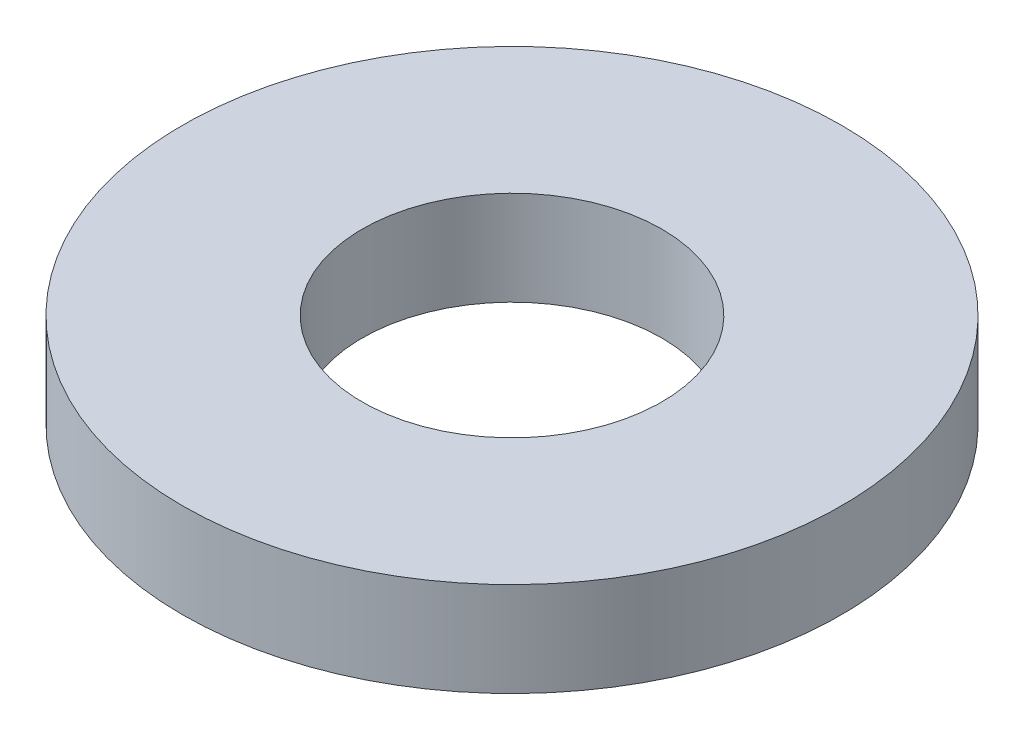
SolidWorks part; units mm, degrees
material "AISI 1020"
ref_plane "Front Plane" through (0, 0, 0) normal (0, 0, 1) x (1, 0, 0)
ref_plane "Top Plane" through (0, 0, 0) normal (0, 1, 0) x (1, 0, 0)
ref_plane "Right Plane" through (0, 0, 0) normal (1, 0, 0) x (0, 0, -1)
sketch "Sketch1" plane through (0, 0, 0) normal (0, 0, 1) x (1, 0, 0)
  line L0 (0, 0) -> (0, 1.6002) construction
  line L1 (2.54, 1.6002) -> (5.588, 1.6002)
  line L2 (2.54, 1.6002) -> (2.54, 0)
  line L3 (2.54, 0) -> (5.588, 0)
  line L4 (5.588, 1.6002) -> (5.588, 0)
  dimension "D1" = 5.08
  dimension "D2" = 11.176
  dimension "D3" = 1.6002
revolve "Revolve1" add sketch "Sketch1" angle 360 about L0
